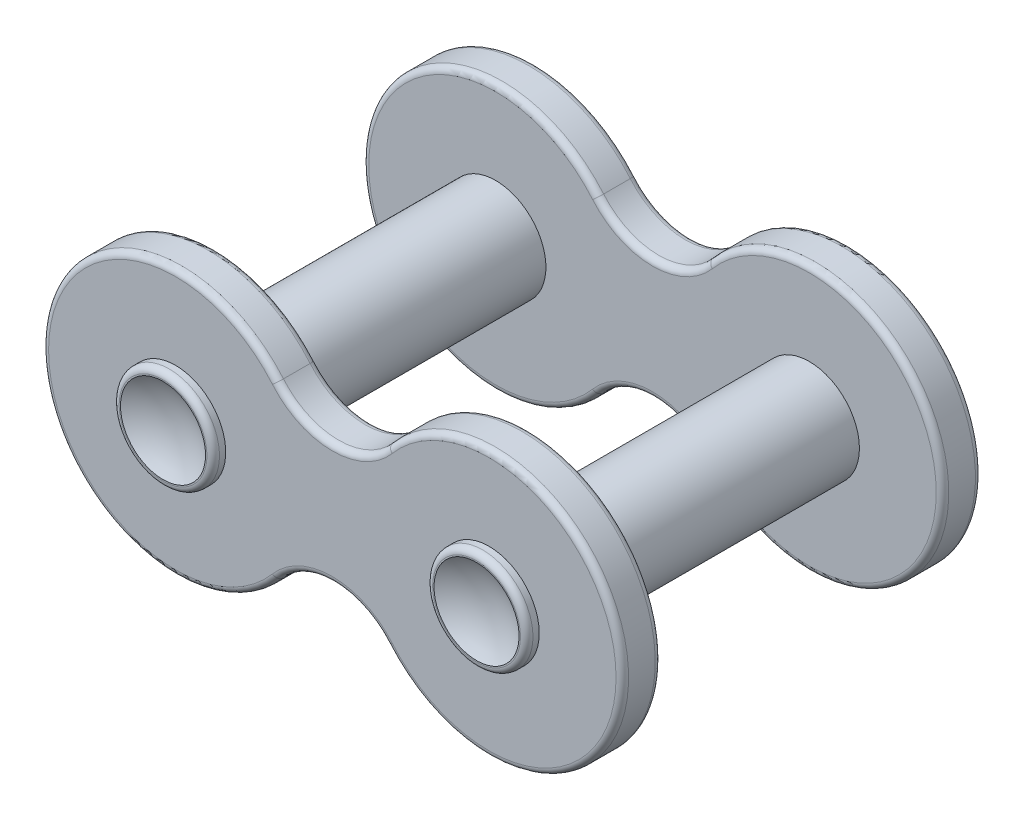
SolidWorks part; units mm, degrees
ref_plane "Front Plane" through (0, 0, 0) normal (0, 0, 1) x (1, 0, 0)
ref_plane "Top Plane" through (0, 0, 0) normal (0, 1, 0) x (1, 0, 0)
ref_plane "Right Plane" through (0, 0, 0) normal (1, 0, 0) x (0, 0, -1)
sketch "Sketch1" plane through (0, 0, 0) normal (0, 0, 1) x (1, 0, 0)
  line L0 (-74.4338, 0) -> (3647.2567, 0) construction
  line L1 (0, -74.4338) -> (0, 3647.2567) construction
  arc A0 (1.4646, -2.2896) -> (1.4646, 2.2896) centre (4.1667, 0) ccw
  circle A1 centre (4.1667, 0) radius 1.3333
  circle A2 centre (-4.1667, 0) radius 1.3333
  arc A3 (-1.4646, -2.2896) -> (-1.4646, 2.2896) centre (-4.1667, 0) cw
  arc A4 (-1.4646, 2.2896) -> (1.4646, 2.2896) centre (0, 3.5306) ccw
  arc A5 (-1.4646, -2.2896) -> (1.4646, -2.2896) centre (0, -3.5306) cw
  dimension "D1" = 7.0833
  dimension "D2" = 2.6667
  dimension "D3" = 4.1667
extrude "Boss-Extrude1" add sketch "Sketch1" along normal blind 1.0417
sketch "Sketch2" plane through (0, 0, 0) normal (0, 0, -1) x (-1, 0, 0)
  circle A0 centre (4.1667, 0) radius 1.3333 construction
  circle A1 centre (4.1667, 0) radius 1.3333
extrude "Boss-Extrude2" add sketch "Sketch2" against normal blind 9.8853 and the other way blind 0.3333
ref_plane "Plane1" through (0, 0, 4.776) normal (0, 0, -1) x (-1, 0, 0)
mirror "Mirror1" about plane through (0, 0, 4.776) normal (0, 0, -1) of "Boss-Extrude1"
sketch "Sketch3" plane through (0, 0, 0) normal (0, 1, 0) x (1, 0, 0)
  line L0 (-4.1667, -9.552) -> (-4.1667, -11.6353) construction
  line L1 (-5.5, -9.552) -> (-2.8333, -9.552) construction
  line L2 (-4.1667, -9.552) -> (-4.1667, -10.5937)
  line L3 (-4.1667, -10.5937) -> (-5.9709, -10.5937)
  arc A0 (-4.1667, -9.552) -> (-5.9709, -10.5937) centre (-4.1667, -11.6353) ccw
  dimension "D1" = 1.0417
  dimension "D2" = 4.1667
revolve "Cut-Revolve1" cut sketch "Sketch3" angle 360 about L0
mirror "Mirror2" about plane through (0, 0, 0) normal (1, 0, 0) of "Cut-Revolve1", "Boss-Extrude2"
mirror "Mirror3" about plane through (0, 0, 4.776) normal (0, 0, -1) of "Cut-Revolve1"
mirror "Mirror4" about plane through (0, 0, 0) normal (1, 0, 0) of "Mirror3"
fillet "Fillet1" radius 0.1667 4 edges at (-5.5, 0, -0.3333) (5.5, 0, -0.3333) (5.5, 0, 9.8853) (-5.5, 0, 9.8853)
fillet "Fillet2" radius 0.1667 16 edges at (0, -1.6109, 1.0417) (-7.7083, 0, 1.0417) (0, 1.6109, 1.0417) (0, -1.6109, 0) (-7.7083, 0, 0) (0, 1.6109, 0) (0, -1.6109, 8.5103) (-7.7083, 0, 8.5103) (0, 1.6109, 8.5103) (0, -1.6109, 9.552) (-7.7083, 0, 9.552) (0, 1.6109, 9.552) (7.7083, 0, 1.0417) (7.7083, 0, 0) (7.7083, 0, 8.5103) (7.7083, 0, 9.552)
